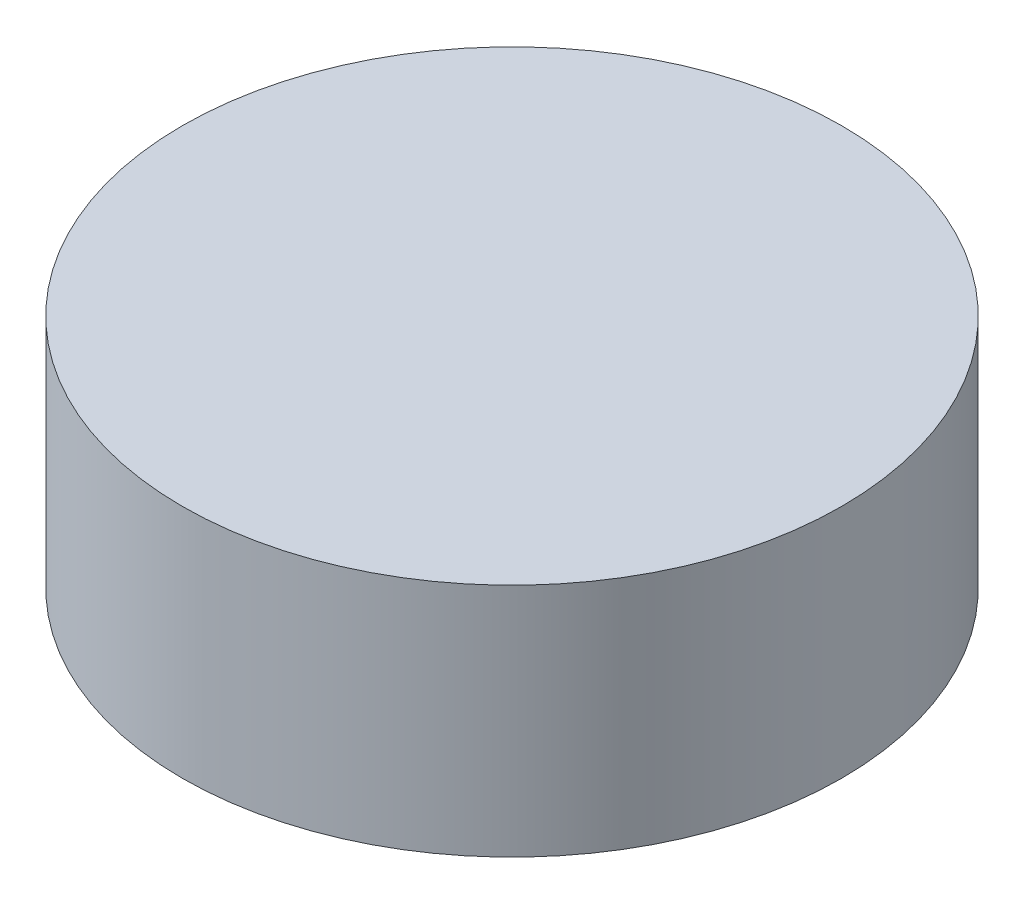
SolidWorks part; units mm, degrees
ref_plane "前视基准面" through (0, 0, 0) normal (0, 0, 1) x (1, 0, 0)
ref_plane "上视基准面" through (0, 0, 0) normal (0, 1, 0) x (1, 0, 0)
ref_plane "右视基准面" through (0, 0, 0) normal (1, 0, 0) x (0, 0, -1)
other "Configuration Table"
sketch "草图1" plane through (0, 0, 0) normal (0, 1, 0) x (1, 0, 0)
  circle A0 centre (0, 0) radius 7
  dimension "D1" = 14
extrude "凸台-拉伸1" add sketch "草图1" along normal blind 5
